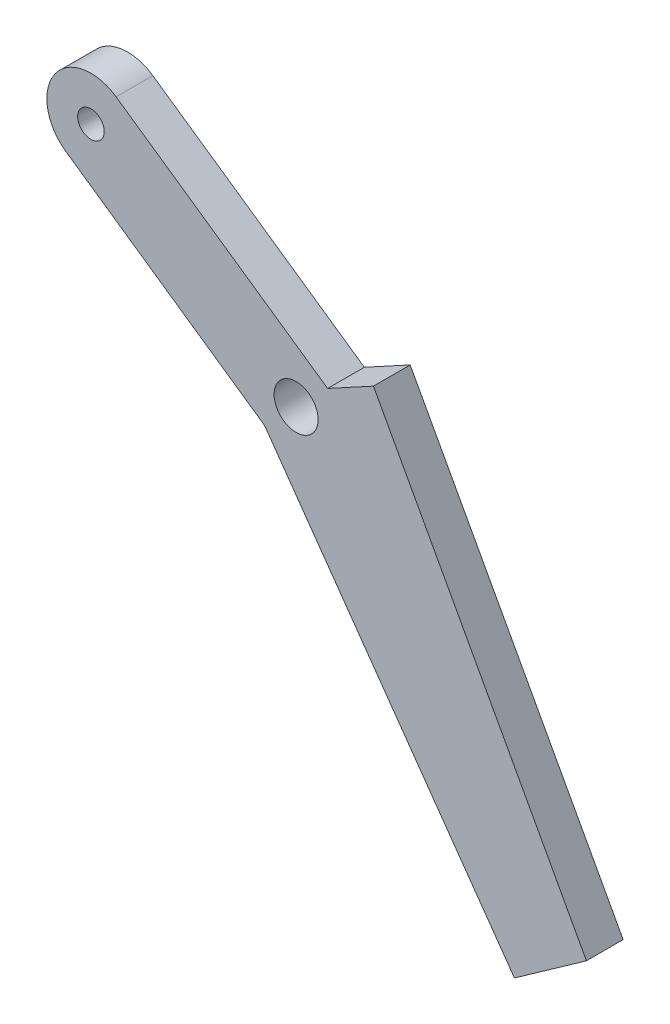
SolidWorks part; units mm, degrees
ref_plane "Alzado" through (0, 0, 0) normal (0, 0, 1) x (1, 0, 0)
ref_plane "Planta" through (0, 0, 0) normal (0, 1, 0) x (1, 0, 0)
ref_plane "Vista lateral" through (0, 0, 0) normal (1, 0, 0) x (0, 0, -1)
sketch "Croquis1" plane through (0, 0, 0) normal (0, 0, 1) x (1, 0, 0)
  line L0 (174.8878, -46.5716) -> (188.8545, -56.2635) construction
  line L1 (188.8545, -56.2635) -> (206.1654, -80.7652) construction
  line L2 (173.1775, -49.0363) -> (186.7095, -58.4266)
  line L3 (176.5982, -44.1069) -> (190.9994, -54.1004)
  line L4 (186.7095, -58.4266) -> (203.7152, -82.4963)
  line L5 (190.9994, -54.1004) -> (208.6155, -79.0341) construction
  line L6 (203.7152, -82.4963) -> (208.6155, -79.0341)
  line L7 (176.5982, -44.1069) -> (190.5648, -53.7988) construction
  line L8 (191.3046, -54.5324) -> (208.6155, -79.0341) construction
  line L9 (186.4043, -57.9946) -> (203.7152, -82.4963) construction
  line L10 (173.1775, -49.0363) -> (187.1441, -58.7282) construction
  line L11 (183.7809, 2.2425) -> (189.4394, -8.3396) construction
  line L12 (183.1195, 1.8888) -> (184.4423, 2.5962) construction
  line L13 (190.1008, -7.986) -> (188.778, -8.6933) construction
  line L14 (189.4394, -8.3396) -> (237.4954, -96.6206) construction
  line L15 (208.6155, -79.0341) -> (194.1186, -52.4025)
  line L16 (190.9994, -54.1004) -> (194.1186, -52.4025)
  circle A0 centre (174.8878, -46.5716) radius 3
  circle A2 centre (174.8878, -46.5716) radius 0.9015
  circle A3 centre (188.8545, -56.2635) radius 1.5
  dimension "D4" = 6
  dimension "D9" = 3
  dimension "D1" = 17
  dimension "D2" = 160
  dimension "D3" = 30
  dimension "D5" = 3
  dimension "D6" = 3
  dimension "D7" = 3
  dimension "D8" = 3
extrude "Saliente-Extruir1" add sketch "Croquis1" along normal blind 2.5 contours A0 L2 L4 L6 L5 L3 | A0 A2
